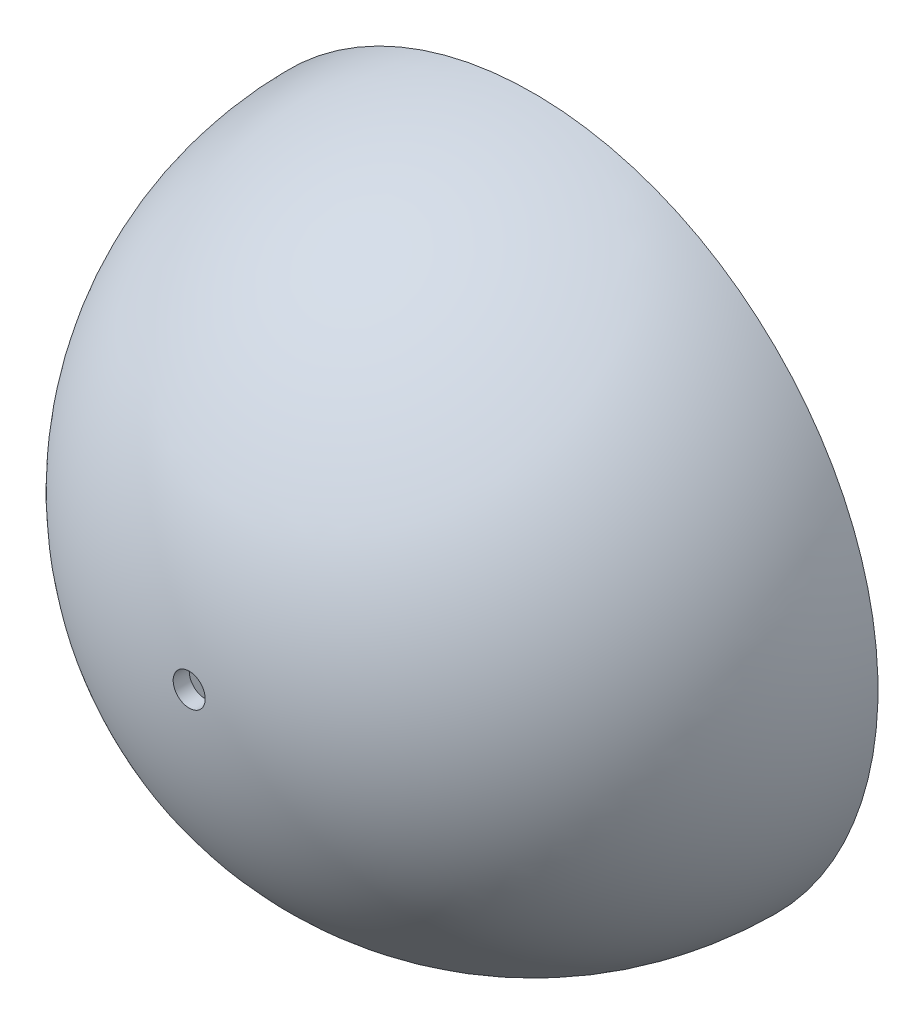
SolidWorks part; units mm, degrees
ref_plane "Front Plane" through (0, 0, 0) normal (0, 0, 1) x (1, 0, 0)
ref_plane "Top Plane" through (0, 0, 0) normal (0, 1, 0) x (1, 0, 0)
ref_plane "Right Plane" through (0, 0, 0) normal (1, 0, 0) x (0, 0, -1)
sketch "Sketch1" plane through (0, 0, 0) normal (0, 0, 1) x (1, 0, 0)
  line L0 (0, 215) -> (0, -215)
  arc A0 (0, -215) -> (0, 215) centre (0, 0) ccw
  dimension "D1" = 430
revolve "Revolve1" add sketch "Sketch1" angle 180 about L0
sketch "Sketch2" plane through (0, 0, 0) normal (0, 0, -1) x (-1, 0, 0)
  line L0 (0, 205) -> (0, -205)
  arc A0 (0, -205) -> (0, 205) centre (0, 0) ccw
  circle A1 centre (0, 0) radius 215 construction
  dimension "D1" = 10
revolve "Cut-Revolve1" cut sketch "Sketch2" angle 180 about L0
sketch "Sketch3" plane through (0, 0, 0) normal (0, 0, 1) x (1, 0, 0)
  circle A0 centre (0, 0) radius 10
  dimension "D1" = 20
extrude "Cut-Extrude1" cut sketch "Sketch3" along normal blind 362
